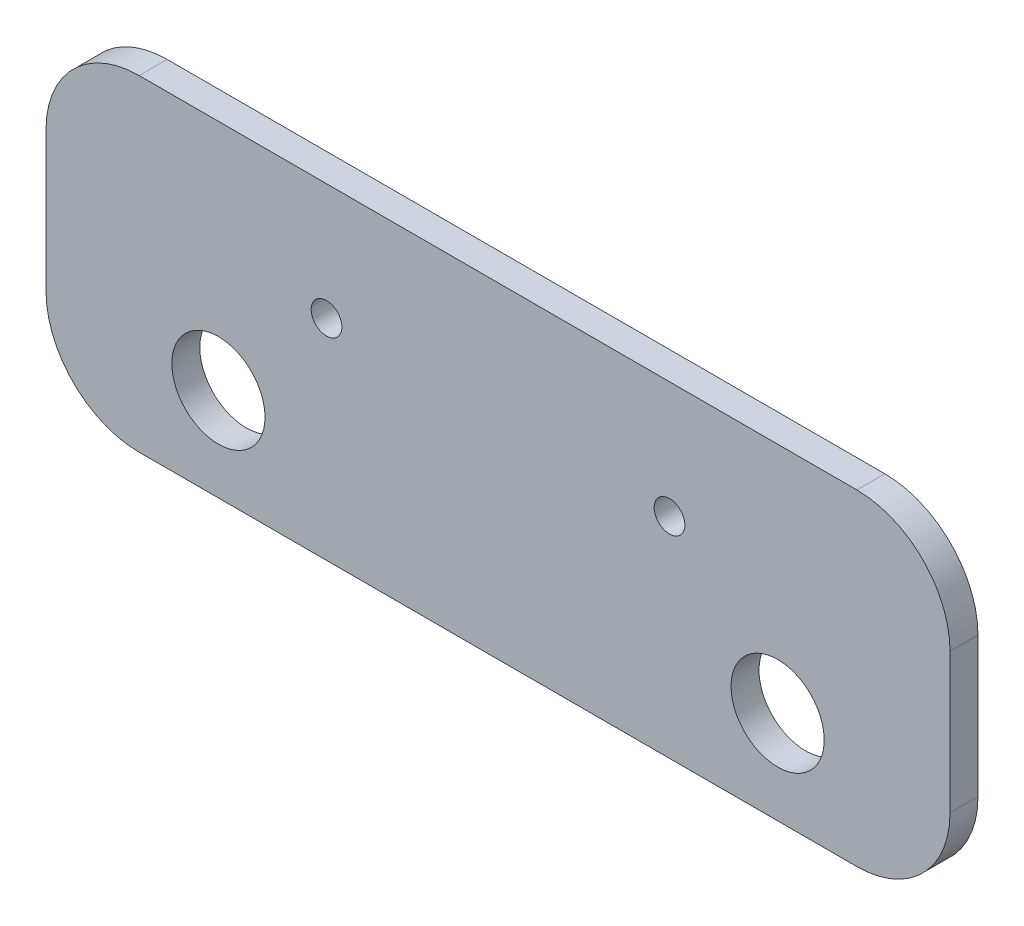
SolidWorks part; units mm, degrees
ref_plane "前视基准面" through (0, 0, 0) normal (0, 0, 1) x (1, 0, 0)
ref_plane "上视基准面" through (0, 0, 0) normal (0, 1, 0) x (1, 0, 0)
ref_plane "右视基准面" through (0, 0, 0) normal (1, 0, 0) x (0, 0, -1)
sketch "草图1" plane through (0, 0, 0) normal (0, 0, 1) x (1, 0, 0)
  line L1 (-45.5, -17.5) -> (45.5, -17.5)
  line L2 (-45.5, -17.5) -> (-45.5, 17.5)
  line L3 (-45.5, 17.5) -> (45.5, 17.5)
  line L4 (45.5, -17.5) -> (45.5, 17.5)
  line L5 (-45.5, -17.5) -> (45.5, 17.5) construction
  line L6 (-45.5, 17.5) -> (45.5, -17.5) construction
  point P0 (0, 0)
  dimension "D1" = 91
  dimension "D2" = 35
extrude "凸台-拉伸2" add sketch "草图1" along normal blind 3
sketch "草图2" plane through (0, 0, 0) normal (0, 0, -1) x (-1, 0, 0)
  circle A0 centre (-22.5, 5) radius 1.25
  circle A1 centre (22.5, 5) radius 1.25
extrude "切除-拉伸1" cut sketch "草图2" against normal blind 3
sketch "草图3" plane through (0, 0, 0) normal (0, 0, -1) x (-1, 0, 0)
  line L0 (45.5, 17.5) -> (45.5, -17.5) construction
  line L1 (-45.5, 17.5) -> (45.5, 17.5)
  line L2 (-45.5, 17.5) -> (-45.5, 14.5)
  line L3 (-45.5, 14.5) -> (45.5, 14.5)
  line L4 (45.5, 17.5) -> (45.5, 14.5)
  dimension "D1" = 3
extrude "凸台-拉伸3" add sketch "草图3" along normal blind 12
sketch "草图4" plane through (45.5, 0, 0) normal (1, 0, 0) x (0, 0, -1)
  line L0 (12, 17.5) -> (24, 17.5)
  line L1 (24, 17.5) -> (24, -17.5)
  line L2 (24, -17.5) -> (-3, -17.5)
  line L3 (-3, -17.5) -> (-3, 17.5)
  line L4 (-3, -17.5) -> (-3, 17.5) construction
  line L5 (-3, 17.5) -> (12, 17.5) construction
  line L6 (-3, 17.5) -> (12, 17.5)
extrude "凸台-拉伸4" add sketch "草图4" along normal blind 3
sketch "草图6" plane through (45.5, 0, 0) normal (-1, 0, 0) x (0, 0, 1)
  circle A0 centre (-20, 9.5) radius 1.25
  circle A1 centre (-20, -15.5) radius 1.25
extrude "切除-拉伸2" cut sketch "草图6" against normal blind 3
sketch "草图7" plane through (-45.5, 0, 0) normal (-1, 0, 0) x (0, 0, 1)
  line L1 (-24, 17.5) -> (3, 17.5)
  line L2 (-24, 17.5) -> (-24, -17.5)
  line L3 (-24, -17.5) -> (3, -17.5)
  line L4 (3, 17.5) -> (3, -17.5)
extrude "凸台-拉伸5" add sketch "草图7" along normal blind 3
sketch "草图8" plane through (-48.5, 0, 0) normal (-1, 0, 0) x (0, 0, 1)
  circle A0 centre (-20, 9.5) radius 1.25
  circle A1 centre (-20, -15.5) radius 1.25
extrude "切除-拉伸3" cut sketch "草图8" against normal blind 3
sketch "草图9" plane through (0, 0, 0) normal (0, 0, -1) x (-1, 0, 0)
  line L0 (-104.5404, 43.4878) -> (97.1357, 67.9972)
  line L1 (-104.5404, 43.4878) -> (-87.5871, -96.0127)
  line L2 (97.1357, 67.9972) -> (114.0891, -71.5033)
  line L3 (-87.5871, -96.0127) -> (114.0891, -71.5033)
extrude "切除-拉伸4" cut sketch "草图9" along normal blind 57.6696
sketch "草图10" plane through (0, 0, 3) normal (0, 0, 1) x (1, 0, 0)
  line L0 (0, -17.5) -> (-30, -17.5)
  line L1 (-48.5, -17.5) -> (48.5, -17.5) construction
  circle A0 centre (-30, -7.5) radius 5
  circle A1 centre (30, -7.5) radius 5
extrude "切除-拉伸5" cut sketch "草图10" against normal blind 57.6696 contours A0 | A1
fillet "圆角1" radius 10 4 edges at (48.5, 17.5, 1.5) (48.5, -17.5, 1.5) (-48.5, 17.5, 1.5) (-48.5, -17.5, 1.5)
sketch "草图11" plane through (0, 0, 3) normal (0, 0, 1) x (1, 0, 0)
  line L0 (0, -17.5) -> (22.5, 5)
  line L1 (-38.5, -17.5) -> (38.5, -17.5) construction
  line L3 (-22.5, 5) -> (0, -17.5)
  line L4 (0, 5) -> (0, -17.5)
  circle A0 centre (18.4, 5) radius 1.65
  circle A1 centre (-18.4, 5) radius 1.65
extrude "切除-拉伸6" cut sketch "草图11" against normal blind 10 contours A0 | A1
sketch "草图12" plane through (0, 0, 3) normal (0, 0, 1) x (1, 0, 0)
  circle A0 centre (22.5, 5) radius 1.25
  circle A1 centre (-22.5, 5) radius 1.25
extrude "凸台-拉伸6" add sketch "草图12" against normal blind 3
